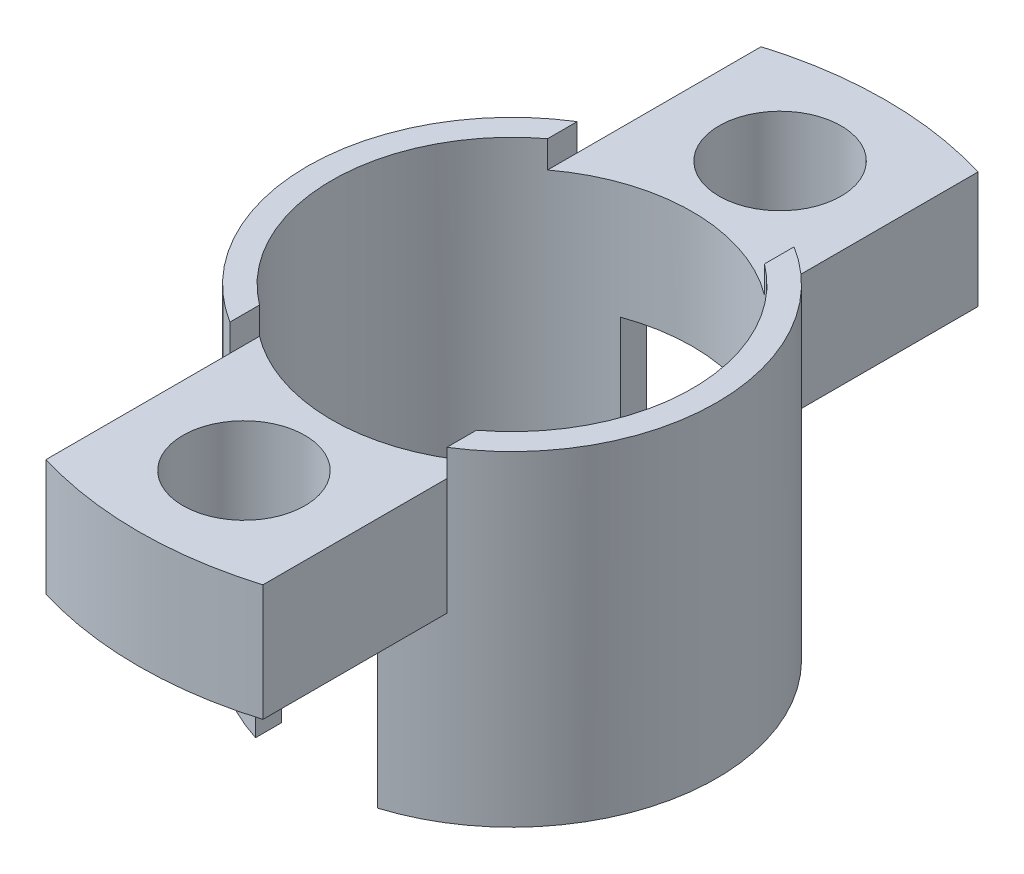
SolidWorks part; units mm, degrees
material "ABS"
ref_plane "Front Plane" through (0, 0, 0) normal (0, 0, 1) x (1, 0, 0)
ref_plane "Top Plane" through (0, 0, 0) normal (0, 1, 0) x (1, 0, 0)
ref_plane "Right Plane" through (0, 0, 0) normal (1, 0, 0) x (0, 0, -1)
sketch "Sketch2" plane through (0, 0, 0) normal (0, 1, 0) x (1, 0, 0)
  circle A0 centre (0, 0) radius 6.55
  circle A1 centre (0, 0) radius 5.8
  dimension "D1" = 13.1
  dimension "D2" = 0.75
extrude "Middle-core" add sketch "Sketch2" along normal blind 6 separate body
ref_plane "Plane for arms" through (0, 5, 0) normal (0, 1, 0) x (1, 0, 0)
sketch "Sketch3" plane through (0, 5, 0) normal (0, 1, 0) x (1, 0, 0)
  line L6 (-4, 5.1868) -> (-4, 13.1868)
  line L7 (-4, 13.1868) -> (4, 13.1868) construction
  line L8 (4, 13.1868) -> (4, 5.1868)
  line L9 (4, -5.1868) -> (4, -13.1868)
  line L10 (4, -13.1868) -> (-4, -13.1868) construction
  line L11 (-4, -13.1868) -> (-4, -5.1868)
  line L12 (0, -13.1868) -> (0, 13.1868) construction
  line L13 (0, -9.8868) -> (0, -13.1868) construction
  line L14 (0, 13.1868) -> (0, 9.8868) construction
  line L15 (0, 7.6368) -> (0, 6.5868) construction
  line L16 (0, 6.5868) -> (0, 12.1368) construction
  line L17 (0, 12.1368) -> (0, 13.1868) construction
  circle A1 centre (0, 9.8868) radius 2.25
  circle A3 centre (0, 0) radius 5.8
  arc A4 (4, -13.1868) -> (-4, -13.1868) centre (0, 0) cw
  arc A5 (-4, 5.1868) -> (-4, -5.1868) centre (0, 0) ccw
  circle A6 centre (0, 0) radius 6.55 construction
  arc A7 (4, -5.1868) -> (4, 5.1868) centre (0, 0) ccw
  circle A8 centre (0, -9.8868) radius 2.25
  circle A10 centre (0, 0) radius 5.8 construction
  arc A11 (-4, 13.1868) -> (4, 13.1868) centre (0, 0) cw
  point P3 (0, 9.8868)
  point P14 (0, 12.1368)
  point P16 (0, 7.6368)
  point P18 (0, -9.8868)
  point P26 (0, -12.1368)
  point P27 (0, -7.6368)
  point P29 (0, 6.5868)
  dimension "D2" = 4.5
  dimension "D1" = 8
  dimension "D3" = 3.3
extrude "Arms_insert-Fixing to guide part" add sketch "Sketch3" against normal blind 4.3
sketch "Sketch1" [suppressed] plane through (0, 0, 0) normal (0, 1, 0) x (1, 0, 0)
  line L0 (-6.2372, -2) -> (-10.2372, -2) construction
  line L1 (-10.2372, -2) -> (-10.2372, 2) construction
  line L2 (-10.2372, 2) -> (-6.2372, 2) construction
  line L3 (6.2372, 2) -> (10.2372, 2) construction
  line L4 (10.2372, 2) -> (10.2372, -2) construction
  line L5 (10.2372, -2) -> (6.2372, -2) construction
  line L6 (-6.55, 0) -> (-10.2372, 0) construction
  line L7 (-6.55, 0) -> (-3.55, 0) construction
  line L8 (-3.55, 0) -> (0, 0) construction
  line L9 (0, 0) -> (3.55, 0) construction
  line L10 (3.55, 0) -> (6.55, 0) construction
  line L11 (6.55, 0) -> (10.2372, 0) construction
  line L13 (-4, -2.1685) -> (-4, 2.1685)
  line L14 (-4, 2.1685) -> (4, 2.1685) construction
  line L15 (4, 2.1685) -> (4, -2.1685)
  line L16 (4, -5.1868) -> (4, -13.1868) construction
  line L17 (-4, -13.1868) -> (-4, -5.1868) construction
  line L18 (-4, -2.1685) -> (-4, -3.8474)
  line L19 (4, -2.1685) -> (4, -3.8474)
  line L20 (-4, 2.1685) -> (-4, 3.8474)
  line L21 (4, 2.1685) -> (4, 3.8474)
  circle A2 centre (0, 0) radius 6.55
  arc A3 (-6.2372, 2) -> (6.2372, 2) centre (0, 0) cw construction
  arc A4 (6.2372, -2) -> (-6.2372, -2) centre (0, 0) cw construction
  arc A5 (-4, -2.1685) -> (-4, 2.1685) centre (0, 0) cw construction
  arc A6 (4, 2.1685) -> (4, -2.1685) centre (0, 0) cw construction
  arc A7 (-4, -3.8474) -> (4, -3.8474) centre (0, 0) ccw
  arc A8 (-4, 3.8474) -> (4, 3.8474) centre (0, 0) cw
  point P15 (10.2372, 0)
  point P20 (-10.2372, 0)
  dimension "D4" = 5.55
  dimension "D1" = 13.1
  dimension "D2" = 4
  dimension "D3" = 4
  dimension "D5" = 1
extrude "Base-hole&toe" [suppressed] add sketch "Sketch1" along normal blind 2
ref_plane "Plane4" [suppressed] through (0, 2, 0) normal (0, 1, 0) x (1, 0, 0)
sketch "Sketch21" [suppressed] plane through (0, 2, 0) normal (0, 1, 0) x (1, 0, 0)
  line L1 (0, 0) -> (3.55, 0) construction
  line L2 (4.0623, -3) -> (12.55, -3)
  line L3 (12.55, -3) -> (12.55, 3)
  line L4 (12.55, 3) -> (4.0623, 3)
  line L5 (-4.0623, 3) -> (-12.55, 3)
  line L6 (-12.55, 3) -> (-12.55, -3)
  line L7 (-12.55, -3) -> (-4.0623, -3)
  line L8 (-12.55, 0) -> (-6.55, 0) construction
  line L9 (-9.55, 3) -> (-9.55, -3) construction
  line L10 (6.55, 0) -> (12.55, 0) construction
  line L11 (9.55, 3) -> (9.55, -3) construction
  line L14 (-6.55, 0) -> (-10.2372, 0) construction
  arc A0 (4.0623, -3) -> (4.0623, 3) centre (0, 0) ccw
  arc A1 (-4.0623, -3) -> (-4.0623, 3) centre (0, 0) cw
  circle A3 centre (-9.55, 0) radius 2
  circle A4 centre (9.55, 0) radius 2
  circle A7 centre (0, 0) radius 6.55 construction
  point P6 (-5.05, 0)
  point P38 (-11.55, 0)
extrude "Arms_hole-Fixing to support part" [suppressed] add sketch "Sketch21" against normal blind 2 separate body
sketch "Sketch22" plane through (0, 5, 0) normal (0, 1, 0) x (1, 0, 0)
  circle A0 centre (0, 0) radius 5.8
  circle A1 centre (0, 0) radius 5.3
  circle A2 centre (0, 0) radius 5.8 construction
  dimension "D1" = 10.6
extrude "Boss-Extrude1" [suppressed] add sketch "Sketch22" along normal up to surface (1 mm away)
sketch "Esquisse1" [suppressed] plane through (0, 0, 0) normal (1, 0, 0) x (0, 0, -1)
  line L1 (-21.6514, 20.4403) -> (22.7117, 20.4403)
  line L2 (-21.6514, 20.4403) -> (-21.6514, -7.7246)
  line L3 (-21.6514, -7.7246) -> (22.7117, -7.7246)
  line L4 (22.7117, 20.4403) -> (22.7117, -7.7246)
extrude "Enlèv. mat.-Extru.1" [suppressed] cut sketch "Esquisse1" along normal through all
sketch "Esquisse2" plane through (0, 0, 0) normal (0, -1, 0) x (1, 0, 0)
  circle A1 centre (0, 0) radius 7.55
  circle A3 centre (0, 0) radius 6.55
  circle A4 centre (0, 0) radius 6.55 construction
  dimension "D1" = 1
extrude "Boss.-Extru.1" add sketch "Esquisse2" against normal up to surface (5 mm away) up to face at (0, 5, -7.6368)
sketch "Esquisse3" plane through (0, 0, 0) normal (0, -1, 0) x (1, 0, 0)
  circle A0 centre (0, 0) radius 6.65
  circle A1 centre (0, 0) radius 7.55
  circle A2 centre (0, 0) radius 7.55 construction
  dimension "D1" = 0.9
extrude "Boss.-Extru.2" add sketch "Esquisse3" along normal blind 6
fillet "Congé4" [suppressed] radius 6
sketch "Esquisse4" [suppressed] plane through (0, 0.7, 0) normal (0, -1, 0) x (1, 0, 0)
  circle A0 centre (0, -9.8868) radius 2.75
  circle A1 centre (0, 9.8868) radius 2.75
  circle A2 centre (0, 9.8868) radius 2.25 construction
  circle A3 centre (0, 9.8868) radius 2.25 construction
  circle A4 centre (0, -9.8868) radius 2.25 construction
  dimension "D1" = 0.5
extrude "Enlèv. mat.-Extru.2" [suppressed] cut sketch "Esquisse4" along normal blind 4
sketch "Sketch23" [suppressed] plane through (0, -6, 0) normal (0, -1, 0) x (1, 0, 0)
  line L0 (25, 25) -> (-25, -25) construction
  line L1 (25, 25) -> (-25, 25)
  line L2 (25, 25) -> (25, -25)
  line L3 (25, -25) -> (-25, -25)
  line L4 (-25, 25) -> (-25, -25)
  line L5 (25, -25) -> (-25, 25) construction
  circle A0 centre (0, 0) radius 7.55
  circle A2 centre (0, 0) radius 7.55 construction
  point P9 (0, 0)
  dimension "D1" = 50
extrude "Cut-Extrude1" [suppressed] cut sketch "Sketch23" against normal blind 4
sketch "Sketch25" plane through (0, 0, 0) normal (0, 1, 0) x (1, 0, 0)
  circle A0 centre (11.5717, 8.8388) radius 7.8078
extrude "Cut-Extrude2" [suppressed] cut sketch "Sketch25" against normal through all both and the other way through all
sketch "Sketch26" plane through (0, -6, 0) normal (0, -1, 0) x (-1, 0, 0)
  line L5 (-2.25, 9.8868) -> (2.25, 9.8868)
  line L6 (-2.25, 9.8868) -> (-2.25, -9.8868)
  line L7 (-2.25, -9.8868) -> (2.25, -9.8868)
  line L8 (2.25, 9.8868) -> (2.25, -9.8868)
  line L9 (-2.25, 9.8868) -> (2.25, -9.8868) construction
  line L10 (-2.25, -9.8868) -> (2.25, 9.8868) construction
  circle A1 centre (0, -9.8868) radius 2.25 construction
  point P0 (0, 0)
extrude "Cut-Extrude3" cut sketch "Sketch26" against normal up to surface (6.7 mm away)
sketch "Sketch27" plane through (0, 6, 0) normal (0, 1, 0) x (1, 0, 0)
  circle A0 centre (0, 0) radius 6.55
  circle A1 centre (0, 0) radius 7.55
extrude "Boss-Extrude2" add sketch "Sketch27" against normal up to surface (1 mm away) up to face at (0, 5, 0)
sketch "Sketch28" plane through (0, 6, 0) normal (0, 1, 0) x (1, 0, 0)
  line L0 (-4, 13.1868) -> (-4, 6.4033) construction
  line L1 (4, -8.7733) -> (-4, -8.7733)
  line L2 (4, -8.7733) -> (4, 8.7733)
  line L3 (4, 8.7733) -> (-4, 8.7733)
  line L4 (-4, -8.7733) -> (-4, 8.7733)
  line L5 (4, -8.7733) -> (-4, 8.7733) construction
  line L6 (4, 8.7733) -> (-4, -8.7733) construction
  point P0 (0, 0)
extrude "Cut-Extrude4" cut sketch "Sketch28" against normal up to surface (1 mm away) up to face at (0, 5, -10.23)
sketch "Sketch29" plane through (0, 0, 0) normal (0, -1, 0) x (1, 0, 0)
  circle A0 centre (0, 0) radius 6.65
extrude "Cut-Extrude5" cut sketch "Sketch29" against normal blind 10
equation "\"magnet_DI\"= 3mm'inner diameter of the o-ring magnet"
equation "\"magnet_DE\"= 8mm'external diameter of the o-ring magnet"
equation "\"magnet_H\"= 3mm'tall of the magnet"
equation "\"magnet_levitation_DI\"= 0mm'inner diameter of the o-ring magnet"
equation "\"magnet_levitation_DE\"= 1mm'external diameter of the o-ring magnet"
equation "\"magnet_levitation_H\"= 0.5mm'tall of the magnet"
equation "\"gap_magnet_H\"= 1mm'gap between the 2 magnets"
equation "\"plug_DI\"= 1.5mm'size of the inner extrude of the plug (finger contact)"
equation "\"coil_H\"= 8mm 'height coil"
equation "\"coil_W\"= 0.2mm 'width coil"
equation "\"mandrine_freegap\"= 0.2mm 'gap between the magnet and the mandrine. "
equation "\"mandrine_bottom_H\"= 0.5mm 'border of the bottom of the mandrine"
equation "\"mandrine_coilmagnet_wall\"= 0.15mm"
equation "\"mandrine_magnet_lev\"= 3mm' gap needed for the levitation of the rod"
equation "\"mandrine_border_H\"= 2mm 'border of the top of the mandrine"
equation "\"mandrine_epoxy_W\"= 0.5mm 'width epoxy"
equation "\"mandrine_DI\"= \"mandrine_freegap\"*2+\"magnet_DE\""
equation "\"mandrine_DE\"= (\"mandrine_epoxy_W\"+\"coil_W\"+\"mandrine_coilmagnet_wall\")*2+\"mandrine_DI\""
equation "\"mandrine_H\"= \"magnet_levitation_H\"+\"mandrine_magnet_lev\"+\"magnet_H\"+\"gap_magnet_H\"/2+\"coil_H\"/2+\"mandrine_border_H\""
equation "\"mandrine_hat_W\"= 1mm"
equation "\"tower_freegap\"= 1mm 'gap between the actuator and the tower"
equation "\"tower_DI\"= \"mandrine_DE\"+\"tower_freegap\""
equation "\"tower_W\"= 1mm'width of the tower"
equation "\"tower_link_H\"= 2mm"
equation "\"tower_link_W\"= 4mm"
equation "\"tower_channel_W\"= 1mm"
equation "\"tower_renforcement_H\"= 2mm"
equation "\"apex_tower_Dbase\"= 2.5mm 'diameter of the holes in order to curve"
equation "\"apex_tower_Rbase1\"= 0.75mm 'diameter of the holes in order to curve"
equation "\"apex_tower_Rbase2\"= 1mm 'diameter of the holes in order to curve"
equation "\"apex_tower_Rbase3\"= 1.25mm 'diameter of the holes in order to curve"
equation "\"apex_tower_holeOpening1\"= \"apex_tower_Rbase1\"*7/8"
equation "\"apex_tower_holeOpening2\"= \"apex_tower_Rbase2\"*7/8"
equation "\"apex_tower_holeOpening3\"= \"apex_tower_Rbase3\"*7/8"
equation "\"apex_tower_Hbase\"= 1mm 'gap between the bottom of the tower and the holes"
equation "\"apex_tower_hole\"= 4.5mm 'witdh of the hole"
equation "\"apex_tower_H\"= 0mm '\"mandrine_H\"-\"tower_link_H\""
equation "\"apex_tower_H2\"= \"apex_tower_H\"+7mm"
equation "\"actuator1.x\"= 42.59mm"
equation "\"actuator2.x\"= 80.026mm"
equation "\"actuator3.x\"= 0mm"
equation "\"actuator4.x\"= 14.55mm"
equation "\"actuator5.x\"= 14.557mm"
equation "\"actuator6.x\"= 12.497mm"
equation "\"actuator7.x\"= 27.494mm"
equation "\"actuator8.x\"= 39.75mm"
equation "\"actuator9.x\"= 41.5767mm"
equation "\"actuator10.x\"= 41.148mm"
equation "\"actuator11.x\"= 70.869mm"
equation "\"actuator12.x\"= 77.15mm"
equation "\"actuator13.x\"= 70.87mm"
equation "\"actuator14.x\"= 80.15mm"
equation "\"actuator15.x\"= 92.21mm"
equation "\"actuator16.x\"= 97.61mm"
equation "\"actuator17.x\"= 87.41mm"
equation "\"actuator18.x\"= 109.08mm"
equation "\"actuator19.x\"= 125.04mm"
equation "\"actuator20.x\"= 119.466mm"
equation "\"actuator21.x\"= 115.558mm"
equation "\"actuator22.x\"= 142.74mm"
equation "\"actuator23.x\"= 145.93mm"
equation "\"actuator24.x\"= 131.11mm"
equation "\"actuator1.y\"= 101.167mm"
equation "\"actuator2.y\"= 120.647mm"
equation "\"actuator3.y\"= 45.677mm"
equation "\"actuator4.y\"= 66.047mm"
equation "\"actuator5.y\"= 45.327mm"
equation "\"actuator6.y\"= 28.807mm"
equation "\"actuator7.y\"= 13.807mm"
equation "\"actuator8.y\"= 30.087mm"
equation "\"actuator9.y\"= 49.157mm"
equation "\"actuator10.y\"= 71.787mm"
equation "\"actuator11.y\"= 78.407mm"
equation "\"actuator12.y\"= 52.377mm"
equation "\"actuator13.y\"= 25.793mm"
equation "\"actuator14.y\"= 0.711mm"
equation "\"actuator15.y\"= 34.092mm"
equation "\"actuator16.y\"= 57.427mm"
equation "\"actuator17.y\"= 86.987mm"
equation "\"actuator18.y\"= 92.077mm"
equation "\"actuator19.y\"= 63.187mm"
equation "\"actuator20.y\"= 34.434mm"
equation "\"actuator21.y\"= 0mm"
equation "\"actuator22.y\"= 38.901mm"
equation "\"actuator23.y\"= 70.278mm"
equation "\"actuator24.y\"= 100.8741mm"
equation "\"actuator1.z\"= 45.834mm"
equation "\"actuator2.z\"= 37.834mm"
equation "\"actuator3.z\"= 13mm"
equation "\"actuator4.z\"= 33.9226mm"
equation "\"actuator5.z\"= 51.234mm"
equation "\"actuator6.z\"= 29.9773mm"
equation "\"actuator7.z\"= 49.434mm"
equation "\"actuator8.z\"= 31.7209mm"
equation "\"actuator9.z\"= 60.084mm"
equation "\"actuator10.z\"= 45.3632mm"
equation "\"actuator11.z\"= 42.0948mm"
equation "\"actuator12.z\"= 33.6927mm"
equation "\"actuator13.z\"= 48.7255mm"
equation "\"actuator14.z\"= 45.0141mm"
equation "\"actuator15.z\"= 63.034mm"
equation "\"actuator16.z\"= 50.5713mm"
equation "\"actuator17.z\"= 61.634mm"
equation "\"actuator18.z\"= 46.3531mm"
equation "\"actuator19.z\"= 57.834mm"
equation "\"actuator20.z\"= 58.534mm"
equation "\"actuator21.z\"= 44.984mm"
equation "\"actuator22.z\"= 45.5969mm"
equation "\"actuator23.z\"= 42.2671mm"
equation "\"actuator24.z\"= 33.4578mm"
equation "\"shape_freegap\"= \"tower_freegap\""
equation "\"shape_strip_witdh\"= 5mm"
equation "\"shape_holes_sweat_D\"= 2mm"
equation "\"shape_holes_actuator_D\"= \"magnet_DE\"+\"shape_freegap\"+1mm"
equation "\"shape_holes_actuator_extD\"= \"shape_holes_actuator_D\"+2*\"shape_strip_witdh\""
equation "\"shape_holes_wet_D\"= 2mm"
equation "\"amortisseur_Dext\"= 18mm"
equation "\"amortisseur_Din\"= 7mm"
equation "\"amortisseur_H\"= 20mm"
equation "\"amortisseur_prise_D\"= 10mm"
equation "\"amortisseur_bourlet_H\"= 0.5mm"
equation "\"fixation_prise_base_D\"= (\"amortisseur_prise_D\"+3)"
equation "\"fixation_prise_base_H\"= 1mm"
equation "\"fixation_prise_tete_D\"= (\"amortisseur_Dext\"+3)"
equation "\"fixation_prise_tete_H\"= 2.5mm"
equation "\"fixation_D\"= \"fixation_prise_tete_D\" + 2mm"
equation "\"fixation_H\"= \"fixation_prise_base_H\" + \"fixation_prise_tete_H\" + 3mm"
equation "\"fixation_zone_accroche_D\"= 3*\"fixation_D\""
equation "\"oring_R\"= 0.75mm"
equation "\"oring_R1\"= 0.25mm"
equation "\"oring_R2\"= 0.3mm"
equation "\"oring_R3\"= 0.75mm"
equation "\"guide_H1\"=4mm"
equation "\"guide_H2\"=1mm"
equation "\"guide_W1\"=1mm"
equation "\"guide_openAngle\"=360deg"
equation "\"guide_ecrou_DI\"=5mm"
equation "\"guide_ecrou_DE\"=8mm"
equation "\"guide_vis_DI\"=4mm"
equation "\"guide_rondelle_DE\"=9mm"
equation "\"D1@Sketch1\"=\"tower_DI\"+\"tower_W\"*2"
equation "\"D1@Base-hole&toe\" = \"tower_link_H\""
equation "\"D1@Middle-core\"=\"mandrine_H\"-\"mandrine_border_H\"/2-6"
equation "\"D4@Sketch1\"=(\"mandrine_DE\"+\"tower_freegap\")/2"
equation "\"D2@Sketch3\"=4.5"
equation "\"D2@Sketch2\"=\"tower_W\"*0.75"
equation "\"D1@Sketch22\"=\"mandrine_DE\"+\"tower_freegap\"/2"
equation "\"D1@Sketch2\"=\"tower_DI\"+\"tower_W\"*2"
